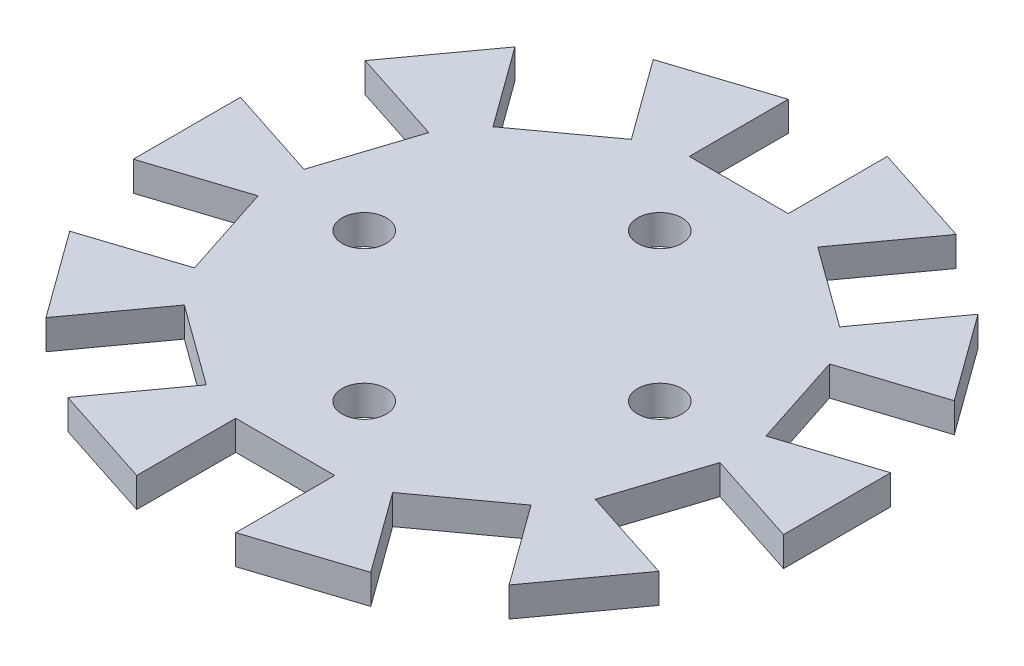
SolidWorks part; units mm, degrees
ref_plane "Front Plane" through (0, 0, 0) normal (0, 0, 1) x (1, 0, 0)
ref_plane "Top Plane" through (0, 0, 0) normal (0, 1, 0) x (1, 0, 0)
ref_plane "Right Plane" through (0, 0, 0) normal (1, 0, 0) x (0, 0, -1)
sketch "Sketch1" plane through (0, 0, 0) normal (0, 1, 0) x (1, 0, 0)
  line L1 (0, 23.1322) -> (-13.5967, 18.7143)
  line L2 (-13.5967, 18.7143) -> (-22, 7.1482)
  line L3 (-22, 7.1482) -> (-22, -7.1482)
  line L4 (-22, -7.1482) -> (-13.5967, -18.7143)
  line L5 (-13.5967, -18.7143) -> (0, -23.1322)
  line L6 (0, -23.1322) -> (13.5967, -18.7143)
  line L7 (13.5967, -18.7143) -> (22, -7.1482)
  line L8 (22, -7.1482) -> (22, 7.1482)
  line L9 (22, 7.1482) -> (13.5967, 18.7143)
  line L10 (13.5967, 18.7143) -> (0, 23.1322)
  circle A0 centre (0, 0) radius 22 construction
  dimension "D1" = 44
extrude "Boss-Extrude1" add sketch "Sketch1" along normal blind 2
sketch "Sketch2" plane through (0, 2, 0) normal (0, 1, 0) x (1, 0, 0)
  line L0 (0, 23.1322) -> (-3.35, 22.0437)
  line L1 (0, 23.1322) -> (-13.5967, 18.7143) construction
  line L2 (-3.35, 22.0437) -> (-3.35, 15.3437)
  line L3 (-3.35, 15.3437) -> (3.35, 15.3437)
  line L4 (3.35, 15.3437) -> (3.35, 22.0437)
  line L5 (13.5967, 18.7143) -> (0, 23.1322) construction
  line L6 (3.35, 22.0437) -> (0, 23.1322)
  line L7 (11.729, 10.4442) -> (15.6672, 15.8646)
  line L8 (15.6672, 15.8646) -> (13.5967, 18.7143)
  line L9 (13.5967, 18.7143) -> (10.2467, 19.8028)
  line L10 (10.2467, 19.8028) -> (6.3086, 14.3824)
  line L11 (6.3086, 14.3824) -> (11.729, 10.4442)
  line L12 (15.6279, 1.5554) -> (22, 3.6258)
  line L13 (22, 3.6258) -> (22, 7.1482)
  line L14 (22, 7.1482) -> (19.9296, 9.9979)
  line L15 (19.9296, 9.9979) -> (13.5575, 7.9275)
  line L16 (13.5575, 7.9275) -> (15.6279, 1.5554)
  line L17 (13.5575, -7.9275) -> (19.9296, -9.9979)
  line L18 (19.9296, -9.9979) -> (22, -7.1482)
  line L19 (22, -7.1482) -> (22, -3.6258)
  line L20 (22, -3.6258) -> (15.6279, -1.5554)
  line L21 (15.6279, -1.5554) -> (13.5575, -7.9275)
  line L22 (6.3086, -14.3824) -> (10.2467, -19.8028)
  line L23 (10.2467, -19.8028) -> (13.5967, -18.7143)
  line L24 (13.5967, -18.7143) -> (15.6672, -15.8646)
  line L25 (15.6672, -15.8646) -> (11.729, -10.4442)
  line L26 (11.729, -10.4442) -> (6.3086, -14.3824)
  line L27 (-3.35, -15.3437) -> (-3.35, -22.0437)
  line L28 (-3.35, -22.0437) -> (0, -23.1322)
  line L29 (0, -23.1322) -> (3.35, -22.0437)
  line L30 (3.35, -22.0437) -> (3.35, -15.3437)
  line L31 (3.35, -15.3437) -> (-3.35, -15.3437)
  line L32 (-11.729, -10.4442) -> (-15.6672, -15.8646)
  line L33 (-15.6672, -15.8646) -> (-13.5967, -18.7143)
  line L34 (-13.5967, -18.7143) -> (-10.2467, -19.8028)
  line L35 (-10.2467, -19.8028) -> (-6.3086, -14.3824)
  line L36 (-6.3086, -14.3824) -> (-11.729, -10.4442)
  line L37 (-15.6279, -1.5554) -> (-22, -3.6258)
  line L38 (-22, -3.6258) -> (-22, -7.1482)
  line L39 (-22, -7.1482) -> (-19.9296, -9.9979)
  line L40 (-19.9296, -9.9979) -> (-13.5575, -7.9275)
  line L41 (-13.5575, -7.9275) -> (-15.6279, -1.5554)
  line L42 (-13.5575, 7.9275) -> (-19.9296, 9.9979)
  line L43 (-19.9296, 9.9979) -> (-22, 7.1482)
  line L44 (-22, 7.1482) -> (-22, 3.6258)
  line L45 (-22, 3.6258) -> (-15.6279, 1.5554)
  line L46 (-15.6279, 1.5554) -> (-13.5575, 7.9275)
  line L47 (-6.3086, 14.3824) -> (-10.2467, 19.8028)
  line L48 (-10.2467, 19.8028) -> (-13.5967, 18.7143)
  line L49 (-13.5967, 18.7143) -> (-15.6672, 15.8646)
  line L50 (-15.6672, 15.8646) -> (-11.729, 10.4442)
  line L51 (-11.729, 10.4442) -> (-6.3086, 14.3824)
  point P5 (0, 15.3437)
  point P59 (0, 0)
  dimension "D1" = 6.7
  dimension "D2" = 6.7
  dimension "D3" = 10
extrude "Cut-Extrude1" cut sketch "Sketch2" against normal up to surface (2 mm away) up to face at (0, 0, 0)
sketch "Sketch7" plane through (0, 2, 0) normal (0, 1, 0) x (1, 0, 0)
  circle A0 centre (0, 0) radius 10 construction
  circle A1 centre (0, 10) radius 1.5
  circle A2 centre (10, 0) radius 1.5
  circle A3 centre (0, -10) radius 1.5
  circle A4 centre (-10, 0) radius 1.5
  dimension "D1" = 20
  dimension "D2" = 3
extrude "Cut-Extrude3" cut sketch "Sketch7" against normal up to surface (2 mm away) up to face at (0, 0, 0)
sketch "Sketch10" plane through (0, 2, 0) normal (0, 1, 0) x (1, 0, 0)
  circle A0 centre (0, 0) radius 2.075
  dimension "D1" = 4.15
extrude "Cut-Extrude6" [suppressed] cut sketch "Sketch10" against normal up to surface (2 mm away)
sketch "Sketch4" plane through (0, 2, 0) normal (0, 1, 0) x (1, 0, 0)
  line L0 (-3.35, 15.3437) -> (3.35, 15.3437) construction
  line L1 (-4.55, 18.9437) -> (4.55, 18.9437)
  line L2 (-4.55, 18.9437) -> (-4.55, 20.5437)
  line L3 (-4.55, 20.5437) -> (4.55, 20.5437)
  line L4 (4.55, 18.9437) -> (4.55, 20.5437)
  line L5 (-4.55, 18.9437) -> (4.55, 20.5437) construction
  line L6 (-4.55, 20.5437) -> (4.55, 18.9437) construction
  line L7 (7.4538, 18.0002) -> (8.3942, 19.2946)
  line L8 (7.4538, 18.0002) -> (14.8158, 12.6513)
  line L9 (14.8158, 12.6513) -> (15.7563, 13.9458)
  line L10 (8.3942, 19.2946) -> (15.7563, 13.9458)
  line L11 (16.6105, 10.1812) -> (18.1322, 10.6757)
  line L12 (16.6105, 10.1812) -> (19.4225, 1.5266)
  line L13 (19.4225, 1.5266) -> (20.9442, 2.021)
  line L14 (18.1322, 10.6757) -> (20.9442, 2.021)
  line L15 (19.4225, -1.5266) -> (20.9442, -2.021)
  line L16 (19.4225, -1.5266) -> (16.6105, -10.1812)
  line L17 (16.6105, -10.1812) -> (18.1322, -10.6757)
  line L18 (20.9442, -2.021) -> (18.1322, -10.6757)
  line L19 (14.8158, -12.6513) -> (15.7563, -13.9458)
  line L20 (14.8158, -12.6513) -> (7.4538, -18.0002)
  line L21 (7.4538, -18.0002) -> (8.3942, -19.2946)
  line L22 (15.7563, -13.9458) -> (8.3942, -19.2946)
  line L23 (4.55, -18.9437) -> (4.55, -20.5437)
  line L24 (4.55, -18.9437) -> (-4.55, -18.9437)
  line L25 (-4.55, -18.9437) -> (-4.55, -20.5437)
  line L26 (4.55, -20.5437) -> (-4.55, -20.5437)
  line L27 (-7.4538, -18.0002) -> (-8.3942, -19.2946)
  line L28 (-7.4538, -18.0002) -> (-14.8158, -12.6513)
  line L29 (-14.8158, -12.6513) -> (-15.7563, -13.9458)
  line L30 (-8.3942, -19.2946) -> (-15.7563, -13.9458)
  line L31 (-16.6105, -10.1812) -> (-18.1322, -10.6757)
  line L32 (-16.6105, -10.1812) -> (-19.4225, -1.5266)
  line L33 (-19.4225, -1.5266) -> (-20.9442, -2.021)
  line L34 (-18.1322, -10.6757) -> (-20.9442, -2.021)
  line L35 (-19.4225, 1.5266) -> (-20.9442, 2.021)
  line L36 (-19.4225, 1.5266) -> (-16.6105, 10.1812)
  line L37 (-16.6105, 10.1812) -> (-18.1322, 10.6757)
  line L38 (-20.9442, 2.021) -> (-18.1322, 10.6757)
  line L39 (-14.8158, 12.6513) -> (-15.7563, 13.9458)
  line L40 (-14.8158, 12.6513) -> (-7.4538, 18.0002)
  line L41 (-7.4538, 18.0002) -> (-8.3942, 19.2946)
  line L42 (-15.7563, 13.9458) -> (-8.3942, 19.2946)
  point P0 (0, 19.7437)
  point P46 (0, 0)
  dimension "D1" = 9.1
  dimension "D2" = 1.6
  dimension "D3" = 4.4
  dimension "D4" = 10
extrude "Cut-Extrude2" [suppressed] cut sketch "Sketch4" against normal blind 1.6
sketch "Sketch8" plane through (0, 0, 0) normal (0, -1, 0) x (1, 0, 0)
  circle A0 centre (0, 0) radius 13
  dimension "D1" = 26
extrude "Cut-Extrude4" [suppressed] cut sketch "Sketch8" against normal blind 1
sketch "Sketch9" plane through (0, 2, 0) normal (0, 1, 0) x (1, 0, 0)
  circle A0 centre (0, 10) radius 3.05
  circle A1 centre (10, 0) radius 3.05
  circle A2 centre (0, -10) radius 3.05
  circle A3 centre (-10, 0) radius 3.05
  dimension "D1" = 6.1
extrude "Cut-Extrude5" [suppressed] cut sketch "Sketch9" against normal blind 1
equation "\"E\"=10"
